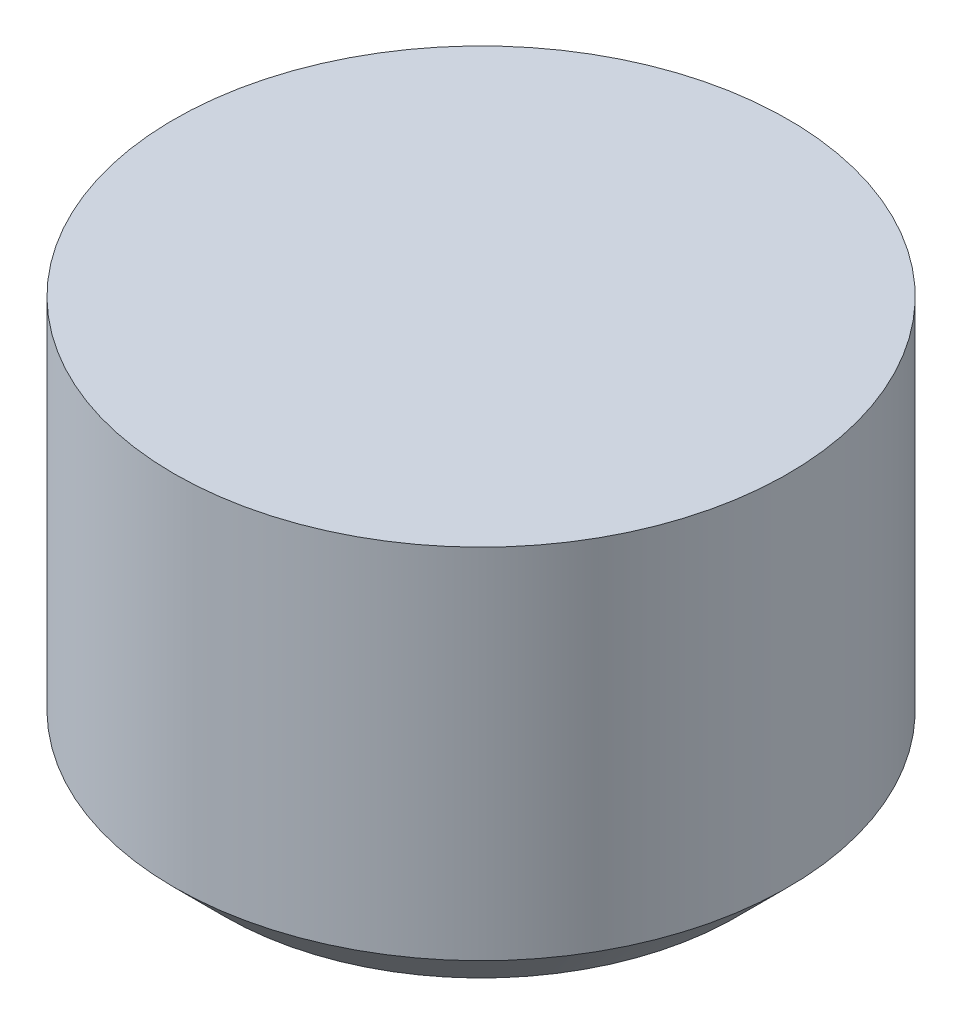
SolidWorks part; units mm, degrees
ref_plane "Front Plane" through (0, 0, 0) normal (0, 0, 1) x (1, 0, 0)
ref_plane "Top Plane" through (0, 0, 0) normal (0, 1, 0) x (1, 0, 0)
ref_plane "Right Plane" through (0, 0, 0) normal (1, 0, 0) x (0, 0, -1)
sketch "Sketch1" plane through (0, 0, 0) normal (0, 1, 0) x (1, 0, 0)
  circle A0 centre (0, 0) radius 9
  dimension "D1" = 18
extrude "Boss-Extrude2" add sketch "Sketch1" along normal blind 12
chamfer "Chamfer1" distance 1.5 angle 45 1 edges at (0, 0, 9)
